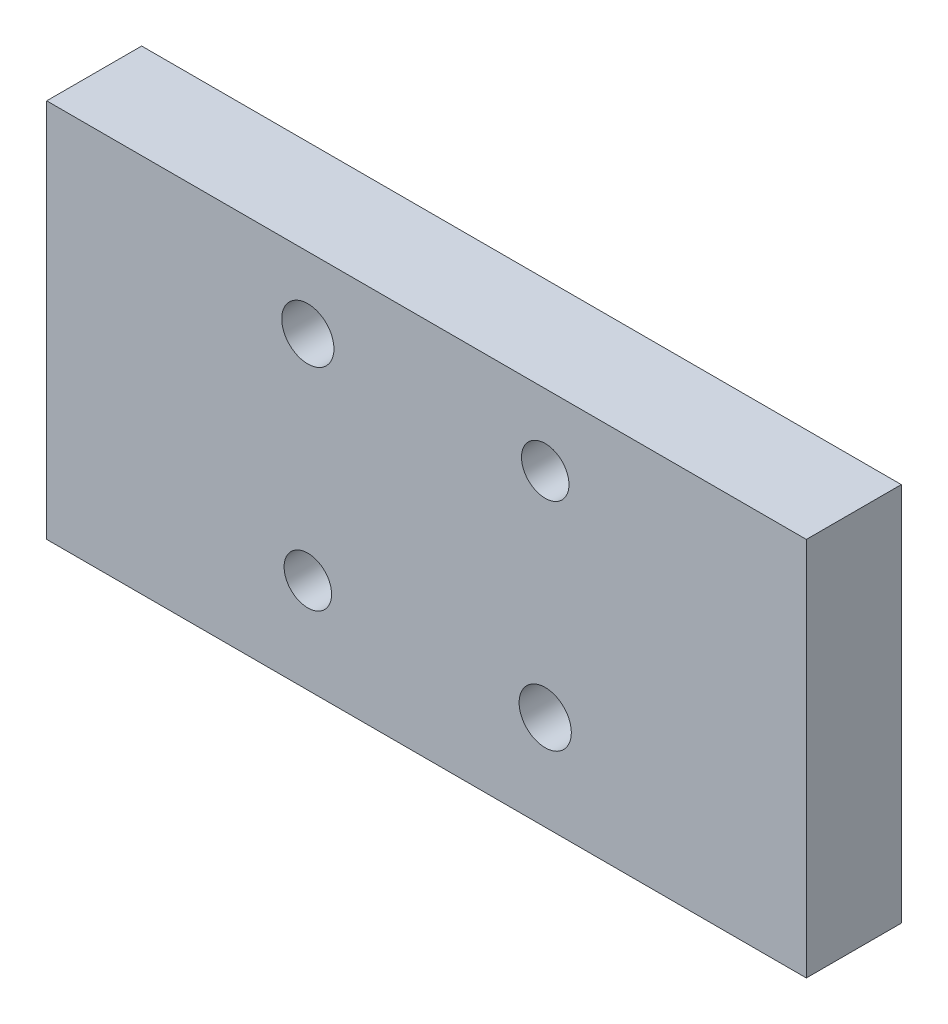
SolidWorks part; units mm, degrees
material "Q235A"
ref_plane "前视" through (0, 0, 0) normal (0, 0, 1) x (1, 0, 0)
ref_plane "上视" through (0, 0, 0) normal (0, 1, 0) x (1, 0, 0)
ref_plane "右视" through (0, 0, 0) normal (1, 0, 0) x (0, 0, -1)
sketch "草图1" plane through (0, 0, 0) normal (0, 0, 1) x (1, 0, 0)
  line L1 (80, -40) -> (-80, -40)
  line L2 (80, -40) -> (80, 40)
  line L3 (80, 40) -> (-80, 40)
  line L4 (-80, -40) -> (-80, 40)
  line L5 (80, -40) -> (-80, 40) construction
  line L6 (80, 40) -> (-80, -40) construction
  point P0 (0, 0)
  dimension "D1" = 80
  dimension "D2" = 160
extrude "凸台-拉伸1" add sketch "草图1" along normal blind 20
hole_wizard "M10 间隙孔1" positions "草图3" profile "草图2" hole size "M10" standard "GB" end condition through all
sketch "草图3" plane through (0, 0, 20) normal (0, 0, 1) x (1, 0, 0)
  line L0 (-80, 40) -> (-80, -40) construction
  line L1 (80, 40) -> (-80, 40) construction
  point P0 (-25, 25)
  point P2 (25, -20)
  dimension "D1" = 55
  dimension "D2" = 50
  dimension "D3" = 15
  dimension "D4" = 45
sketch "草图2" plane through (-25, 25, 20) normal (1, 0, 0) x (0, -1, 0)
  line L0 (0, 0) -> (0, 20)
  line L1 (0, 20) -> (5.5, 20)
  line L2 (5.5, 20) -> (5.5, 0)
  line L5 (5.5, 0) -> (0, 0)
  line L11 (0, -6.35) -> (0, 107.95) construction
  dimension "通孔孔直径" = 11
  dimension "通孔孔深度" = 20
hole_wizard "大小mm 暗销孔1" positions "草图5" profile "草图4" hole size "Ø10.0" standard "GB" end condition through all
sketch "草图5" plane through (0, 0, 20) normal (0, 0, 1) x (1, 0, 0)
  circle A0 centre (-25, 25) radius 5.5 construction
  circle A1 centre (25, -20) radius 5.5 construction
  point P0 (25, 25)
  point P2 (-25, -20)
  dimension "D2" = 50
  dimension "D1" = 45
  dimension "D3" = 45
  dimension "D4" = 50
sketch "草图4" plane through (25, 25, 20) normal (1, 0, 0) x (0, -1, 0)
  line L0 (0, 0) -> (0, 20)
  line L1 (0, 20) -> (5, 20)
  line L2 (5, 20) -> (5, 0)
  line L5 (5, 0) -> (0, 0)
  line L11 (0, -6.35) -> (0, 107.95) construction
  dimension "通孔孔直径" = 10
  dimension "通孔孔深度" = 20
